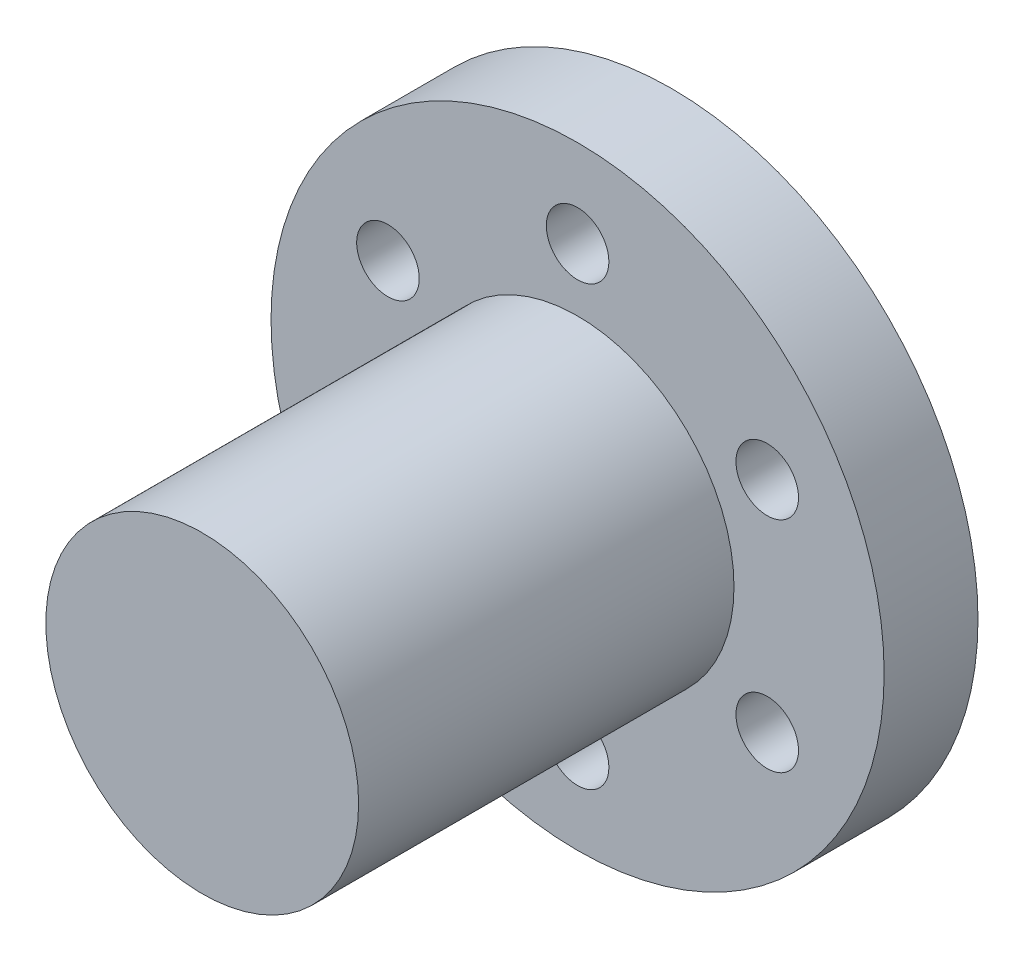
SolidWorks part; units mm, degrees
ref_plane "Front Plane" through (0, 0, 0) normal (0, 0, 1) x (1, 0, 0)
ref_plane "Top Plane" through (0, 0, 0) normal (0, 1, 0) x (1, 0, 0)
ref_plane "Right Plane" through (0, 0, 0) normal (1, 0, 0) x (0, 0, -1)
sketch "Sketch1" plane through (0, 0, 0) normal (0, 0, 1) x (1, 0, 0)
  circle A0 centre (0, 0) radius 1244.6
  dimension "D1" = 2489.2
extrude "Boss-Extrude1" add sketch "Sketch1" along normal mid plane 381
sketch "Sketch2" plane through (0, 0, 190.5) normal (0, 0, 1) x (1, 0, 0)
  circle A0 centre (0, 0) radius 889 construction
  circle A1 centre (0, 889) radius 127
  circle A2 centre (769.8966, 444.5) radius 127
  circle A3 centre (769.8966, -444.5) radius 127
  circle A4 centre (0, -889) radius 127
  circle A5 centre (-769.8966, -444.5) radius 127
  circle A6 centre (-769.8966, 444.5) radius 127
  circle A7 centre (0, 0) radius 1244.6 construction
  point P17 (0, 0)
  dimension "D1" = 1778
  dimension "D2" = 254
  dimension "D3" = 6
extrude "Cut-Extrude1" cut sketch "Sketch2" against normal through all
sketch "Sketch3" plane through (0, 0, 190.5) normal (0, 0, 1) x (1, 0, 0)
  circle A0 centre (0, 0) radius 635
  dimension "D1" = 1270
extrude "Boss-Extrude2" add sketch "Sketch3" along normal blind 1524
sketch "Sketch6" plane through (0, 0, 1714.5) normal (0, 0, 1) x (1, 0, 0)
  line L0 (0, 1244.6) -> (0, -1244.6) construction
  line L1 (-1163.7635, 0) -> (1163.7635, 0) construction
  line L2 (-278.2936, 946.9758) -> (-1163.7635, 0)
  line L3 (-1163.7635, 0) -> (-278.2936, -946.9758)
  line L4 (278.2936, -946.9758) -> (1163.7635, 0)
  line L5 (1163.7635, 0) -> (278.2936, 946.9758)
  arc A0 (278.2936, -946.9758) -> (-278.2936, -946.9758) centre (0, -686.7573) cw
  arc A1 (278.2936, 946.9758) -> (-278.2936, 946.9758) centre (0, 686.7573) ccw
  dimension "D1" = 381
